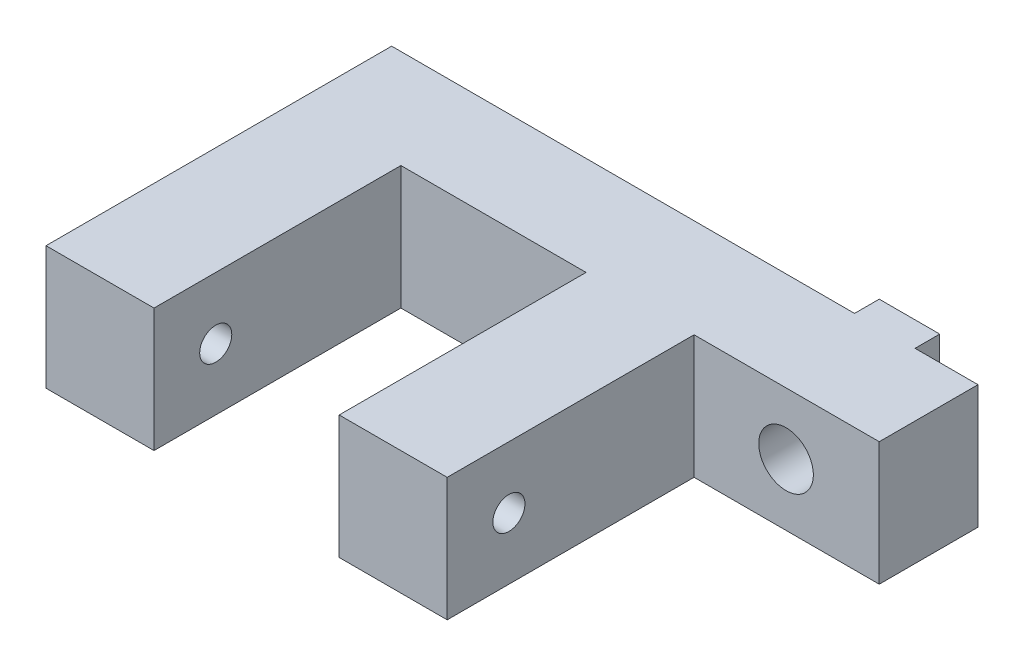
SolidWorks part; units mm, degrees
ref_plane "Front" through (0, 0, 0) normal (0, 0, 1) x (1, 0, 0)
ref_plane "Top" through (0, 0, 0) normal (0, 1, 0) x (1, 0, 0)
ref_plane "Right" through (0, 0, 0) normal (1, 0, 0) x (0, 0, -1)
sketch "Sketch1" plane through (0, 0, 0) normal (0, 1, 0) x (1, 0, 0)
  line L0 (47.625, 0) -> (53.848, 0)
  line L1 (41.275, -12.7) -> (41.275, -38.1)
  line L2 (41.275, -38.1) -> (30.1625, -38.1)
  line L3 (30.1625, -38.1) -> (30.1625, -12.7)
  line L4 (30.1625, -12.7) -> (11.1125, -12.7)
  line L5 (11.1125, -12.7) -> (11.1125, -38.1)
  line L6 (11.1125, -38.1) -> (0, -38.1)
  line L7 (0, -38.1) -> (0, -2.54)
  line L8 (41.275, -12.7) -> (60.325, -12.7)
  line L9 (60.325, -12.7) -> (60.325, -2.54)
  line L10 (0, -2.54) -> (47.625, -2.54)
  line L11 (47.625, -2.54) -> (47.625, 0)
  line L12 (53.848, 0) -> (53.848, -2.54)
  line L13 (53.848, -2.54) -> (60.325, -2.54)
  dimension "D1" = 60.325
  dimension "D2" = 19.05
  dimension "D3" = 38.1
  dimension "D4" = 6.223
  dimension "D5" = 11.1125
  dimension "D6" = 2.54
  dimension "D7" = 47.625
  dimension "D8" = 10.16
extrude "Extrude1" add sketch "Sketch1" along normal mid plane 12.7
hole_wizard "M4x0.7 Tapped Hole1" positions "Sketch4" profile "Sketch3" tap size "M4x0.7" standard "Ansi Metric" end condition through all
sketch "Sketch4" plane through (41.275, 0, 0) normal (1, 0, 0) x (0, 0, -1)
  line L0 (0, 6.35) -> (0, -6.35) construction
  line L1 (-38.1, 6.35) -> (-12.7, 6.35) construction
  point P0 (-31.75, 0)
  dimension "D1" = 31.75
  dimension "D2" = 6.35
cosmetic thread "Hole Thread1" parameters "D2"=4
sketch "Sketch3" plane through (41.275, 0, 31.75) normal (0, 1, 0) x (0, 0, -1)
  line L0 (0, 0) -> (0, 41.275)
  line L1 (0, 41.275) -> (1.65, 41.275)
  line L2 (1.65, 41.275) -> (1.65, 0)
  line L5 (1.65, 0) -> (0, 0)
  line L11 (0, -6.35) -> (0, 107.95) construction
  dimension "Thru Tap Drill Dia." = 3.3
  dimension "Thru Tap Drill Depth" = 41.275
hole_wizard "#10 Clearance Hole1" positions "Sketch6" profile "Sketch5" hole size "#10" standard "Ansi Inch" end condition up to next
sketch "Sketch6" plane through (0, 0, 0) normal (0, 0, -1) x (-1, 0, 0)
  line L3 (-53.848, -6.35) -> (-47.625, -6.35) construction
  line L4 (-47.625, 6.35) -> (-47.625, -6.35) construction
  point P1 (-50.7365, 0)
  dimension "D1" = 3.1115
  dimension "D3" = 6.35
sketch "Sketch5" plane through (50.7365, 0, 0) normal (1, 0, 0) x (0, 1, 0)
  line L0 (0, 0) -> (0, 12.7)
  line L1 (0, 12.7) -> (2.8067, 12.7)
  line L2 (2.8067, 12.7) -> (2.8067, 0)
  line L5 (2.8067, 0) -> (0, 0)
  line L11 (0, -6.35) -> (0, 107.95) construction
  dimension "Thru Hole Dia." = 5.6134
  dimension "Thru Hole Depth" = 12.7
